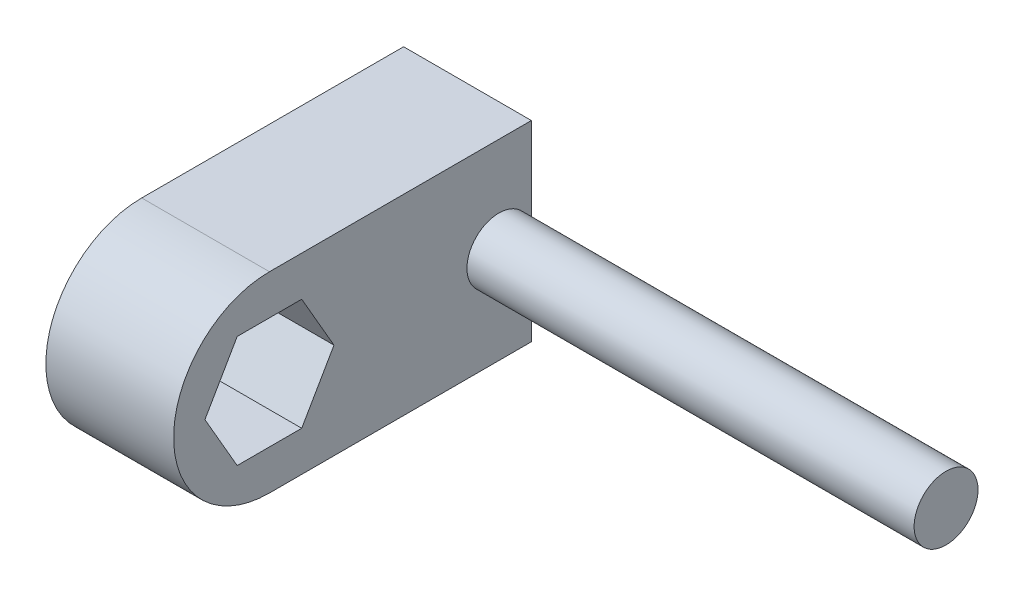
SolidWorks part; units mm, degrees
ref_plane "Front Plane" through (0, 0, 0) normal (0, 0, 1) x (1, 0, 0)
ref_plane "Top Plane" through (0, 0, 0) normal (0, 1, 0) x (1, 0, 0)
ref_plane "Right Plane" through (0, 0, 0) normal (1, 0, 0) x (0, 0, -1)
sketch "Sketch1" plane through (0, 0, 0) normal (1, 0, 0) x (0, 0, -1)
  line L0 (0, 7.5) -> (20.5, 7.5)
  line L1 (5.05, 0) -> (2.525, 4.3734)
  line L2 (2.525, 4.3734) -> (-2.525, 4.3734)
  line L3 (-2.525, 4.3734) -> (-5.05, 0)
  line L4 (-5.05, 0) -> (-2.525, -4.3734)
  line L5 (-2.525, -4.3734) -> (2.525, -4.3734)
  line L6 (2.525, -4.3734) -> (5.05, 0)
  line L7 (20.5, 7.5) -> (20.5, -7.5)
  line L8 (20.5, -7.5) -> (0, -7.5)
  arc A0 (0, 7.5) -> (0, -7.5) centre (0, 0) ccw
  circle A1 centre (0, 0) radius 4.3734 construction
  dimension "D1" = 15
  dimension "D2" = 5.05
  dimension "D3" = 28
extrude "Boss-Extrude1" add sketch "Sketch1" along normal blind 10 contours L1 L2 L3 L4 L5 L6 | A0 L8 L7 L0
sketch "Sketch2" plane through (10, 0, 0) normal (1, 0, 0) x (0, 0, -1)
  circle A0 centre (17.956, 0) radius 2.5
  dimension "D1" = 5
extrude "Boss-Extrude2" add sketch "Sketch2" along normal blind 35
